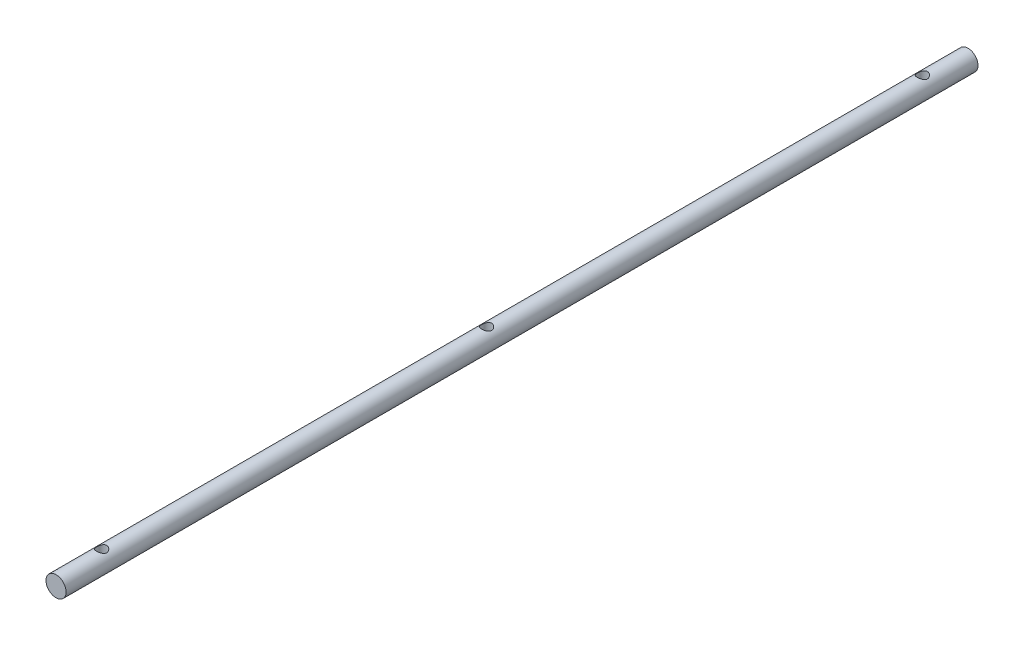
SolidWorks part; units mm, degrees
ref_plane "Front Plane" through (0, 0, 0) normal (0, 0, 1) x (1, 0, 0)
ref_plane "Top Plane" through (0, 0, 0) normal (0, 1, 0) x (1, 0, 0)
ref_plane "Right Plane" through (0, 0, 0) normal (1, 0, 0) x (0, 0, -1)
sketch "Sketch2" plane through (0, 0, 0) normal (0, 0, 1) x (1, 0, 0)
  circle A0 centre (0, 0) radius 1.985
  dimension "D1" = 3.97
extrude "Boss-Extrude1" add sketch "Sketch2" along normal blind 180
sketch "Sketch4" plane through (0, 0, 0) normal (0, 1, 0) x (1, 0, 0)
  line L0 (0, -180) -> (0, -171) construction
  line L1 (-1.985, -180) -> (1.985, -180) construction
  line L2 (0, 0) -> (0, -9) construction
  line L3 (0, -180) -> (0, -95.02) construction
  circle A0 centre (0, -171) radius 1
  circle A1 centre (0, -9) radius 1
  circle A2 centre (0, -95.02) radius 1
  dimension "D2" = 2
  dimension "D4" = 2
  dimension "D6" = 2
  dimension "D1" = 9
  dimension "D3" = 9
  dimension "D5" = 84.98
extrude "Cut-Extrude1" cut sketch "Sketch4" against normal through all both and the other way through all
